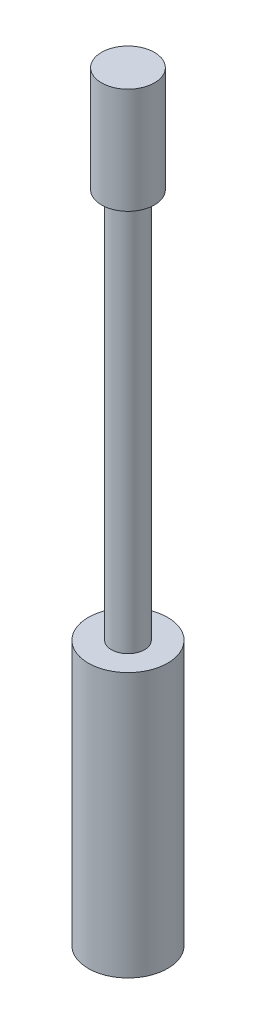
SolidWorks part; units mm, degrees
material "Gray Cast Iron"
ref_plane "Front Plane" through (0, 0, 0) normal (0, 0, 1) x (1, 0, 0)
ref_plane "Top Plane" through (0, 0, 0) normal (0, 1, 0) x (1, 0, 0)
ref_plane "Right Plane" through (0, 0, 0) normal (1, 0, 0) x (0, 0, -1)
sketch "Sketch1" plane through (0, 0, 0) normal (0, 1, 0) x (1, 0, 0)
  circle A0 centre (0, 0) radius 6
  dimension "D1" = 12
extrude "Boss-Extrude1" add sketch "Sketch1" along normal blind 40
sketch "Sketch2" plane through (0, 40, 0) normal (0, 1, 0) x (1, 0, 0)
  circle A0 centre (0, 0) radius 2.5
  dimension "D1" = 5
extrude "Boss-Extrude2" add sketch "Sketch2" along normal blind 59
sketch "Sketch3" plane through (0, 99, 0) normal (0, 1, 0) x (1, 0, 0)
  circle A0 centre (0, 0) radius 4
  dimension "D1" = 8
extrude "Boss-Extrude3" add sketch "Sketch3" along normal blind 16
